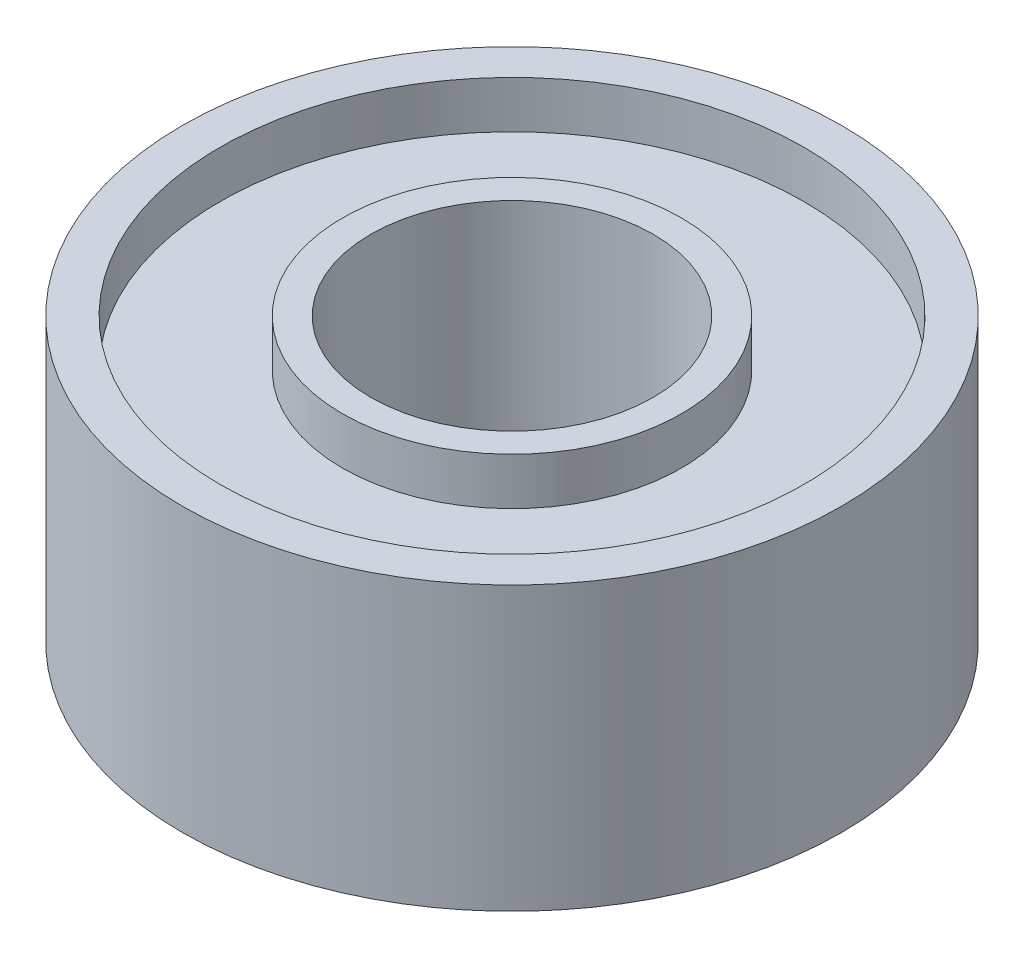
SolidWorks part; units mm, degrees
material "AISI 304"
ref_plane "前视基准面" through (0, 0, 0) normal (0, 0, 1) x (1, 0, 0)
ref_plane "上视基准面" through (0, 0, 0) normal (0, 1, 0) x (1, 0, 0)
ref_plane "右视基准面" through (0, 0, 0) normal (1, 0, 0) x (0, 0, -1)
sketch "草图1" plane through (0, 0, 0) normal (0, 1, 0) x (1, 0, 0)
  circle A0 centre (0, 0) radius 3.5
  circle A1 centre (0, 0) radius 1.5
extrude "凸台-拉伸1" add sketch "草图1" along normal blind 3
sketch "草图2" plane through (0, 3, 0) normal (0, 1, 0) x (1, 0, 0)
  circle A0 centre (0, 0) radius 1.8
  circle A1 centre (0, 0) radius 3.1
extrude "切除-拉伸1" cut sketch "草图2" against normal blind 0.5
ref_plane "基准面1" through (0, 1.5, 0) normal (0, 1, 0) x (1, 0, 0)
mirror "镜向1" about plane through (0, 1.5, 0) normal (0, 1, 0) of "切除-拉伸1"
